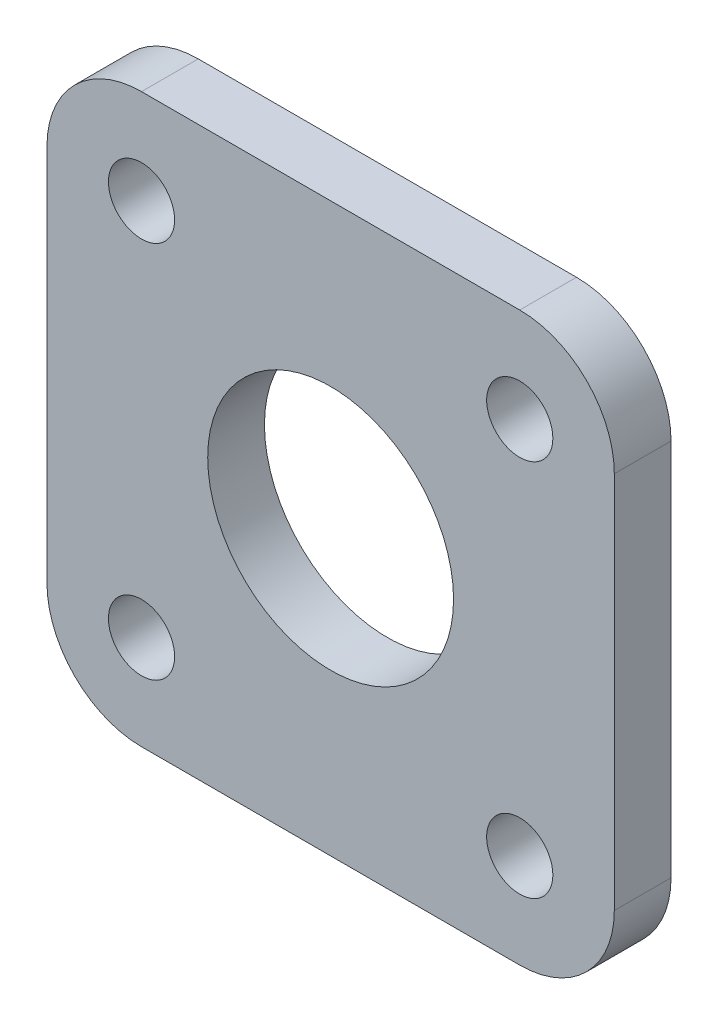
SolidWorks part; units mm, degrees
ref_plane "Front Plane" through (0, 0, 0) normal (0, 0, 1) x (1, 0, 0)
ref_plane "Top Plane" through (0, 0, 0) normal (0, 1, 0) x (1, 0, 0)
ref_plane "Right Plane" through (0, 0, 0) normal (1, 0, 0) x (0, 0, -1)
sketch "Sketch1" plane through (0, 0, 0) normal (0, 0, 1) x (1, 0, 0)
  line L1 (-10, 10) -> (10, 10) construction
  line L2 (-10, 10) -> (-10, -10) construction
  line L3 (-10, -10) -> (10, -10) construction
  line L4 (10, 10) -> (10, -10) construction
  line L5 (-10, 10) -> (10, -10) construction
  line L6 (-10, -10) -> (10, 10) construction
  line L7 (-10, 15) -> (10, 15)
  line L8 (-15, 10) -> (-15, -10)
  line L9 (-10, -15) -> (10, -15)
  line L10 (15, 10) -> (15, -10)
  line L11 (-15, 15) -> (15, -15) construction
  line L12 (-15, -15) -> (15, 15) construction
  circle A0 centre (0, 0) radius 6.5
  circle A1 centre (-10, 10) radius 1.75
  circle A2 centre (10, 10) radius 1.75
  circle A3 centre (10, -10) radius 1.75
  circle A4 centre (-10, -10) radius 1.75
  arc A5 (-15, -10) -> (-10, -15) centre (-10, -10) ccw
  arc A6 (10, -15) -> (15, -10) centre (10, -10) ccw
  arc A7 (15, 10) -> (10, 15) centre (10, 10) ccw
  arc A8 (-10, 15) -> (-15, 10) centre (-10, 10) ccw
  dimension "D1" = 13
  dimension "D3" = 3.5
  dimension "D5" = 5
  dimension "D2" = 20
  dimension "D4" = 30
extrude "Boss-Extrude1" add sketch "Sketch1" along normal blind 3
